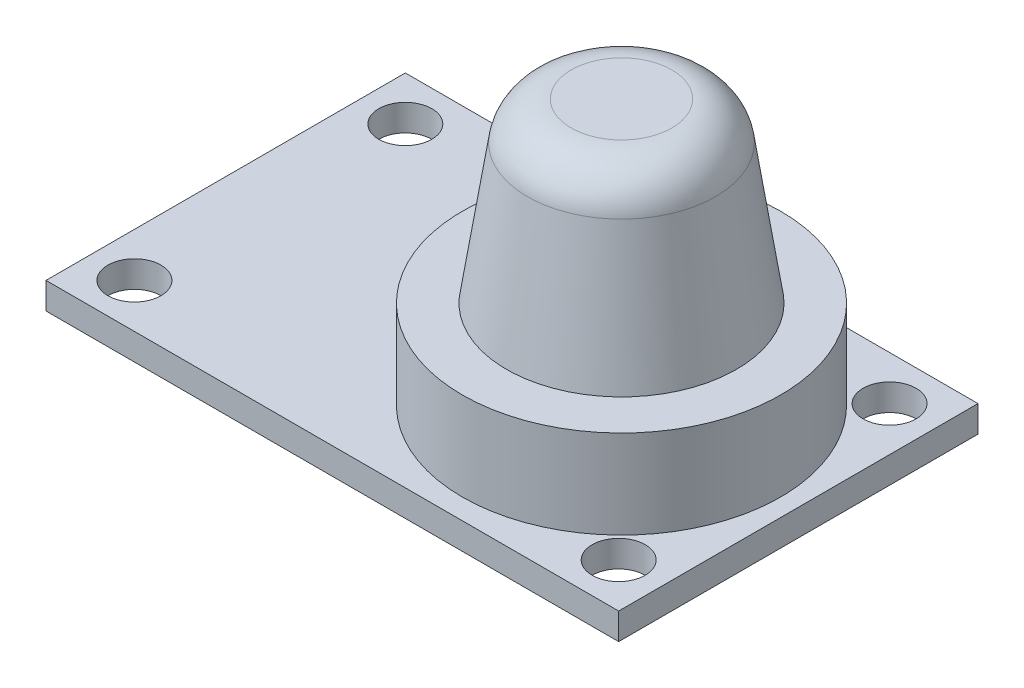
SolidWorks part; units mm, degrees
ref_plane "Front Plane" through (0, 0, 0) normal (0, 0, 1) x (1, 0, 0)
ref_plane "Top Plane" through (0, 0, 0) normal (0, 1, 0) x (1, 0, 0)
ref_plane "Right Plane" through (0, 0, 0) normal (1, 0, 0) x (0, 0, -1)
sketch "Sketch1" plane through (0, 0, 0) normal (0, 1, 0) x (1, 0, 0)
  line L0 (0, -55) -> (0, 55) construction
  line L1 (-16.1925, 10.16) -> (16.1925, 10.16)
  line L2 (-16.1925, 10.16) -> (-16.1925, -10.16)
  line L3 (-16.1925, -10.16) -> (16.1925, -10.16)
  line L4 (16.1925, 10.16) -> (16.1925, -10.16)
  line L5 (-16.1925, 10.16) -> (16.1925, -10.16) construction
  line L6 (-16.1925, -10.16) -> (16.1925, 10.16) construction
  line L7 (-55, 0) -> (55, 0) construction
  circle A0 centre (-13.6925, 7.66) radius 1.5
  circle A1 centre (13.6925, 7.66) radius 1.5
  circle A2 centre (13.6925, -7.66) radius 1.5
  circle A3 centre (-13.6925, -7.66) radius 1.5
  point P0 (0, 0)
  dimension "D3" = 3
  dimension "D1" = 32.385
  dimension "D2" = 20.32
  dimension "D4" = 2.5
  dimension "D5" = 2.5
extrude "Boss-Extrude1" add sketch "Sketch1" along normal blind 1.5
sketch "Sketch2" plane through (0, 1.5, 0) normal (0, 1, 0) x (1, 0, 0)
  line L0 (16.1925, -10.16) -> (16.1925, 10.16) construction
  circle A0 centre (6.1925, 0) radius 9
  point P2 (0, 0)
  point P3 (0, 0)
  point P5 (0, 0)
  dimension "D1" = 18
  dimension "D2" = 10
extrude "Boss-Extrude2" add sketch "Sketch2" along normal blind 5
sketch "Sketch3" plane through (0, 0, 0) normal (0, 0, 1) x (1, 0, 0)
  line L0 (6.1925, 6.5) -> (6.1925, 16.5)
  line L1 (15.1925, 6.5) -> (-2.8075, 6.5) construction
  line L2 (6.1925, 16.5) -> (9.0395, 16.5)
  line L3 (11.5119, 14.3709) -> (12.6925, 6.5)
  line L4 (12.6925, 6.5) -> (6.1925, 6.5)
  arc A0 (9.0395, 16.5) -> (11.5119, 14.3709) centre (9.0395, 14) cw
  point P9 (11.1925, 16.5)
  dimension "D4" = 2.5
  dimension "D1" = 2.5
  dimension "D2" = 5
  dimension "D3" = 10
revolve "Revolve1" add sketch "Sketch3" angle 360 about L0
